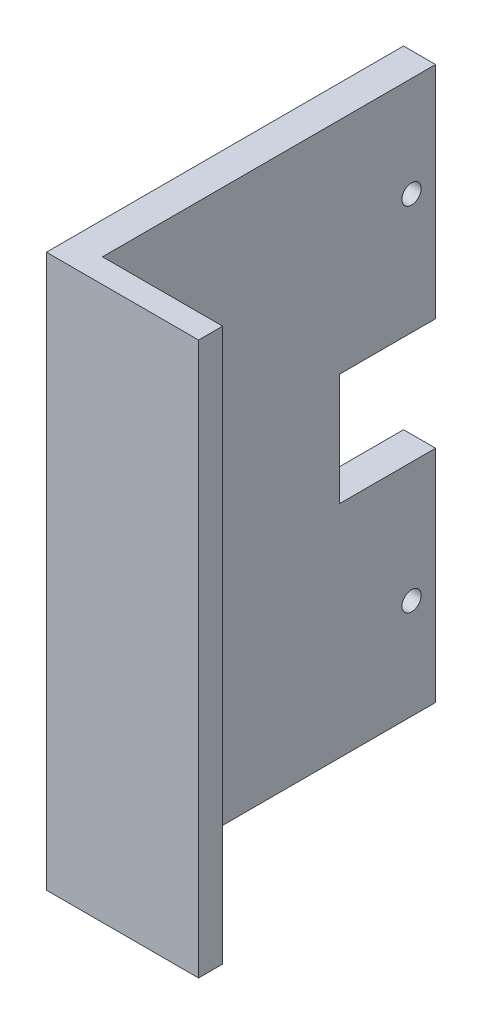
SolidWorks part; units mm, degrees
ref_plane "Front Plane" through (0, 0, 0) normal (0, 0, 1) x (1, 0, 0)
ref_plane "Top Plane" through (0, 0, 0) normal (0, 1, 0) x (1, 0, 0)
ref_plane "Right Plane" through (0, 0, 0) normal (1, 0, 0) x (0, 0, -1)
ref_plane "PZ_p126_200" through (0, 0, 126.2) normal (0, 0, 1) x (1, 0, 0)
sketch "S_box1" plane through (0, 0, 126.2) normal (0, 0, 1) x (1, 0, 0)
  line L0 (10.2, -34.5) -> (14.2, -34.5)
  line L1 (14.2, -34.5) -> (14.2, 34.5)
  line L2 (14.2, 34.5) -> (10.2, 34.5)
  line L3 (10.2, 34.5) -> (10.2, -34.5)
  dimension "P1" = 10.2
  dimension "P2" = 34.5
  dimension "P3" = 14.2
  dimension "P4" = 34.5
  dimension "P5" = 14.2
  dimension "P6" = 34.5
  dimension "P7" = 10.2
  dimension "P8" = 34.5
extrude "Boss_1" add sketch "S_box1" along normal blind 44.6
ref_plane "PZ_p167_800" through (0, 0, 167.8) normal (0, 0, 1) x (1, 0, 0)
sketch "S_box2" plane through (0, 0, 167.8) normal (0, 0, 1) x (1, 0, 0)
  line L0 (10.2, -34.5) -> (29.2, -34.5)
  line L1 (29.2, -34.5) -> (29.2, 34.5)
  line L2 (29.2, 34.5) -> (10.2, 34.5)
  line L3 (10.2, 34.5) -> (10.2, -34.5)
  dimension "P1" = 10.2
  dimension "P2" = 34.5
  dimension "P3" = 29.2
  dimension "P4" = 34.5
  dimension "P5" = 29.2
  dimension "P6" = 34.5
  dimension "P7" = 10.2
  dimension "P8" = 34.5
extrude "Boss_2" add sketch "S_box2" along normal blind 3
ref_plane "PZ_p126_100" through (0, 0, 126.1) normal (0, 0, 1) x (1, 0, 0)
sketch "S_cut3" plane through (0, 0, 126.1) normal (0, 0, 1) x (1, 0, 0)
  line L0 (10.1, -7) -> (14.3, -7)
  line L1 (14.3, -7) -> (14.3, 7)
  line L2 (14.3, 7) -> (10.1, 7)
  line L3 (10.1, 7) -> (10.1, -7)
  dimension "P1" = 10.1
  dimension "P2" = 7
  dimension "P3" = 14.3
  dimension "P4" = 7
  dimension "P5" = 14.3
  dimension "P6" = 7
  dimension "P7" = 10.1
  dimension "P8" = 7
extrude "Pocket_3" cut sketch "S_cut3" along normal blind 12.1
ref_plane "PX_p10_100" through (10.1, 0, 0) normal (1, 0, 0) x (0, 0, -1)
sketch "S_hole4" plane through (10.1, 0, 0) normal (1, 0, 0) x (0, 0, -1)
  circle A0 centre (-129.2, -22) radius 1.2
  dimension "D1_S_hole4" = 2.4
  dimension "P2" = 129.2
  dimension "P3" = 22
extrude "Hole_4" cut sketch "S_hole4" along normal blind 4.2
sketch "S_hole5" plane through (10.1, 0, 0) normal (1, 0, 0) x (0, 0, -1)
  circle A0 centre (-129.2, -22) radius 2.3
  dimension "D1_S_hole5" = 4.6
  dimension "P2" = 129.2
  dimension "P3" = 22
extrude "Hole_5" cut sketch "S_hole5" along normal blind 1.4
sketch "S_hole6" plane through (10.1, 0, 0) normal (1, 0, 0) x (0, 0, -1)
  circle A0 centre (-129.2, 22) radius 1.2
  dimension "D1_S_hole6" = 2.4
  dimension "P2" = 129.2
  dimension "P3" = 22
extrude "Hole_6" cut sketch "S_hole6" along normal blind 4.2
sketch "S_hole7" plane through (10.1, 0, 0) normal (1, 0, 0) x (0, 0, -1)
  circle A0 centre (-129.2, 22) radius 2.3
  dimension "D1_S_hole7" = 4.6
  dimension "P2" = 129.2
  dimension "P3" = 22
extrude "Hole_7" cut sketch "S_hole7" along normal blind 1.4
equation "\"plate_t\" = 3"
equation "\"clearance\" = 0.5"
